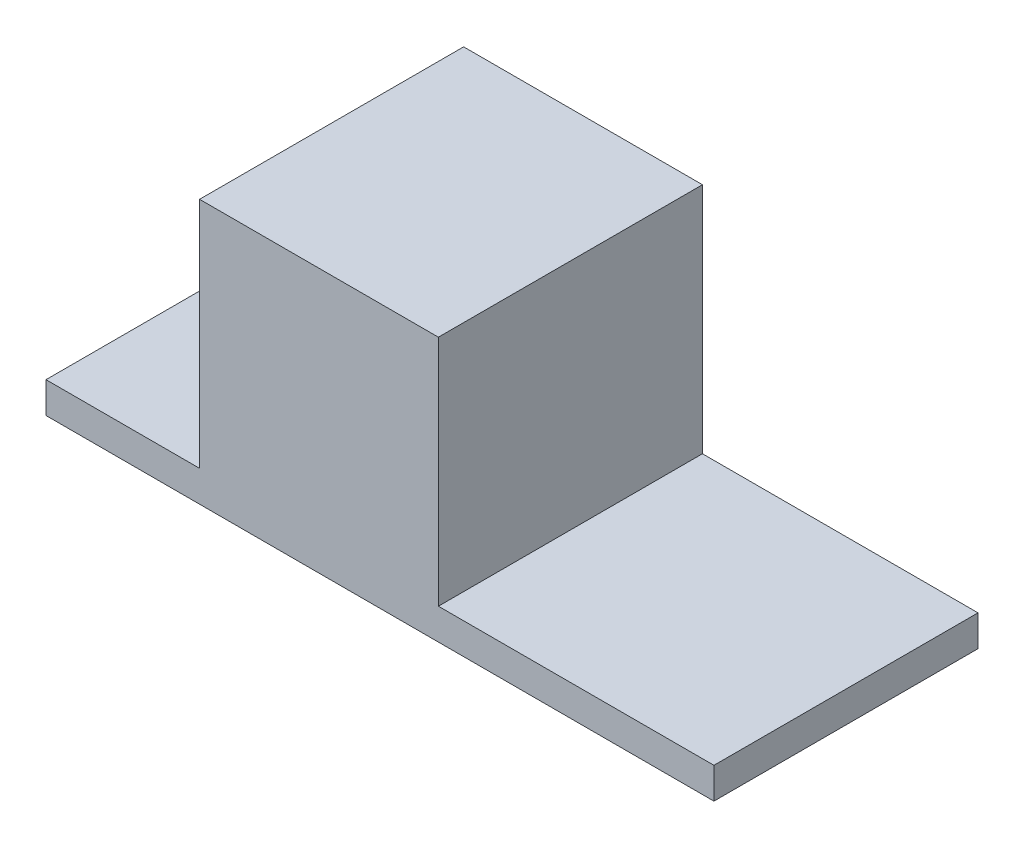
SolidWorks part; units mm, degrees
ref_plane "Front Plane" through (0, 0, 0) normal (0, 0, 1) x (1, 0, 0)
ref_plane "Top Plane" through (0, 0, 0) normal (0, 1, 0) x (1, 0, 0)
ref_plane "Right Plane" through (0, 0, 0) normal (1, 0, 0) x (0, 0, -1)
sketch "Sketch1" plane through (0, 0, 0) normal (0, 1, 0) x (1, 0, 0)
  line L1 (0, 0) -> (43, 0)
  line L2 (0, 0) -> (0, -17)
  line L3 (0, -17) -> (43, -17)
  line L4 (43, 0) -> (43, -17)
  dimension "D1" = 43
  dimension "D2" = 17
extrude "Boss-Extrude1" add sketch "Sketch1" along normal blind 2
sketch "Sketch2" plane through (0, 2, 0) normal (0, 1, 0) x (1, 0, 0)
  line L0 (43, 0) -> (0, 0) construction
  line L1 (9.8871, 0) -> (25.2615, 0)
  line L2 (9.8871, 0) -> (9.8871, -17)
  line L3 (9.8871, -17) -> (25.2615, -17)
  line L4 (25.2615, 0) -> (25.2615, -17)
  line L5 (0, -17) -> (43, -17) construction
extrude "Boss-Extrude2" add sketch "Sketch2" along normal blind 15
